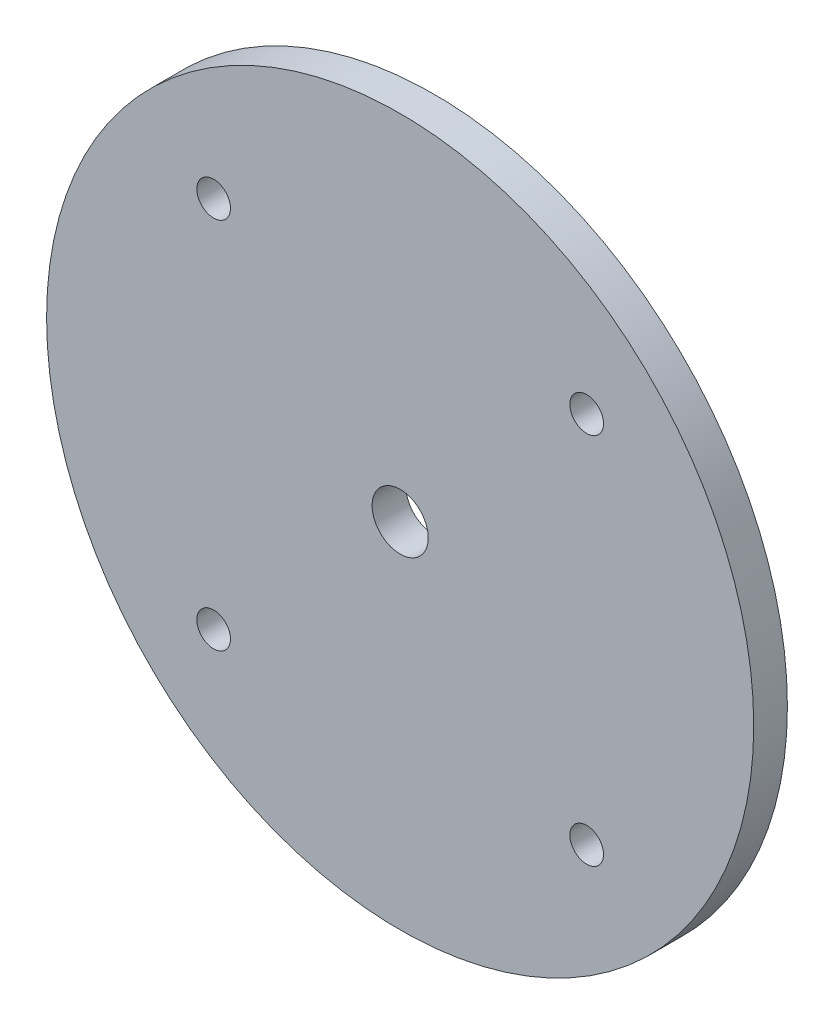
SolidWorks part; units mm, degrees
ref_plane "Alzado" through (0, 0, 0) normal (0, 0, 1) x (1, 0, 0)
ref_plane "Planta" through (0, 0, 0) normal (0, 1, 0) x (1, 0, 0)
ref_plane "Vista lateral" through (0, 0, 0) normal (1, 0, 0) x (0, 0, -1)
sketch "Croquis1" plane through (0, 0, 0) normal (0, 0, 1) x (1, 0, 0)
  line L1 (-21.1753, 30.481) -> (-65.7231, 30.481) construction
  line L3 (-65.7231, -14.0668) -> (-21.1753, -14.0668) construction
  line L4 (-21.1753, -14.0668) -> (-21.1753, 30.481) construction
  line L5 (-21.1753, 30.481) -> (-65.7231, -14.0668) construction
  line L6 (-65.7231, -14.0668) -> (-65.7231, 30.481) construction
  line L7 (-65.7231, 30.481) -> (-21.1753, -14.0668) construction
  circle A0 centre (-43.4492, 8.2071) radius 31.5
  circle A2 centre (-60.0662, 24.8241) radius 1.5
  circle A3 centre (-26.8322, 24.8241) radius 1.5
  circle A4 centre (-26.8322, -8.4099) radius 1.5
  circle A5 centre (-60.0662, -8.4099) radius 1.5
  dimension "D1" = 63
  dimension "D3" = 8
  dimension "D4" = 8
  dimension "D5" = 8
  dimension "D6" = 8
extrude "Saliente-Extruir1" add sketch "Croquis1" along normal blind 3
sketch "Croquis4" plane through (0, 0, 0) normal (0, 0, -1) x (-1, 0, 0)
  circle A0 centre (43.4492, 8.2071) radius 2.5
  dimension "D1" = 5
extrude "Cortar-Extruir3" cut sketch "Croquis4" against normal blind 3
